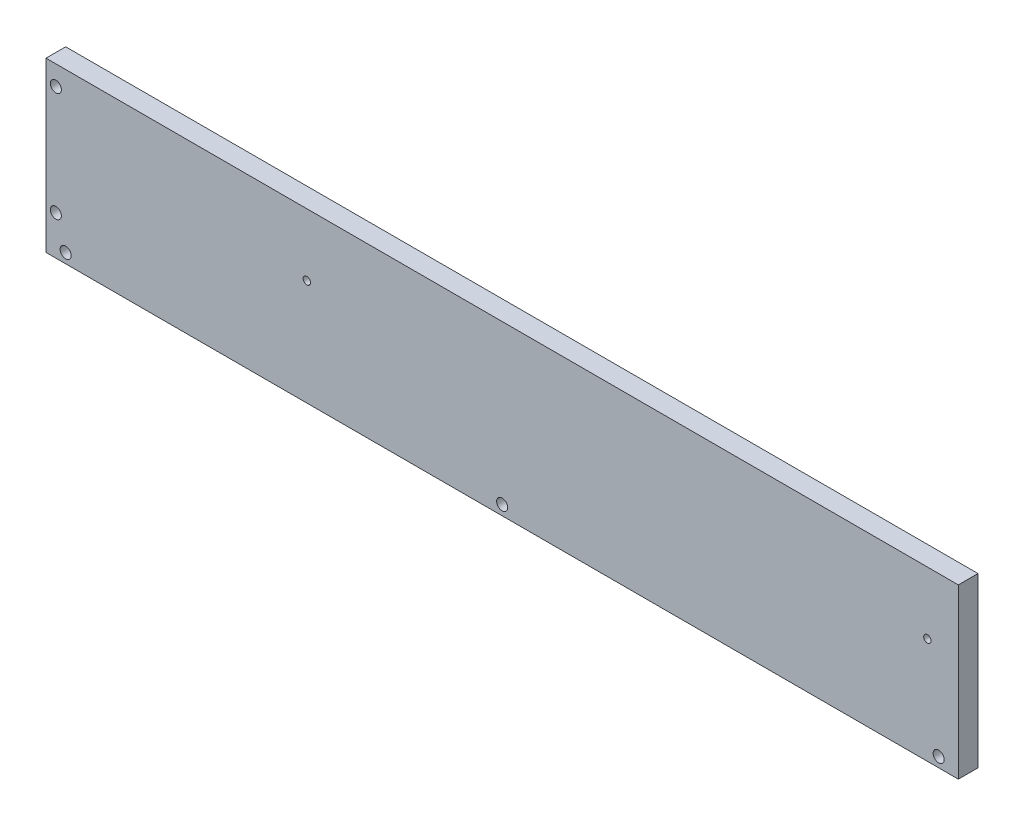
SolidWorks part; units mm, degrees
ref_plane "Front Plane" through (0, 0, 0) normal (0, 0, 1) x (1, 0, 0)
ref_plane "Top Plane" through (0, 0, 0) normal (0, 1, 0) x (1, 0, 0)
ref_plane "Right Plane" through (0, 0, 0) normal (1, 0, 0) x (0, 0, -1)
sketch "Sketch1" plane through (0, 0, 0) normal (0, 0, 1) x (1, 0, 0)
  line L0 (3.175, 48) -> (3.175, 12.7) construction
  line L1 (6.35, 3.175) -> (147.32, 3.175) construction
  line L2 (147.32, 3.175) -> (288.29, 3.175) construction
  circle A0 centre (3.175, 48) radius 1.7859
  circle A1 centre (3.175, 12.7) radius 1.7859
  circle A2 centre (6.35, 3.175) radius 1.7859
  circle A3 centre (288.29, 3.175) radius 1.7859
  circle A4 centre (147.32, 3.175) radius 1.7859
  line B0 (0, 54.35) -> (0, 0)
  line B1 (0, 0) -> (294.64, 0)
  line B2 (294.64, 0) -> (294.64, 54.35)
  line B3 (294.64, 54.35) -> (0, 54.35)
  circle B4 centre (84.24, 34.25) radius 1.1906
  circle B5 centre (284.64, 34.25) radius 1.1906
sketch_block_instance "Left_Side-1"
sketch_block "Left_Side" parameters "D1"=7.6508, "D2"=31.9297, "D3"=3.0553, "D4"=3.0553, "D5"=2.0606, "D6"=11.0921, "D7"=165.4056, "D8"=229.9573
extrude "Boss-Extrude1" add sketch "Sketch1" along normal blind 6.35
